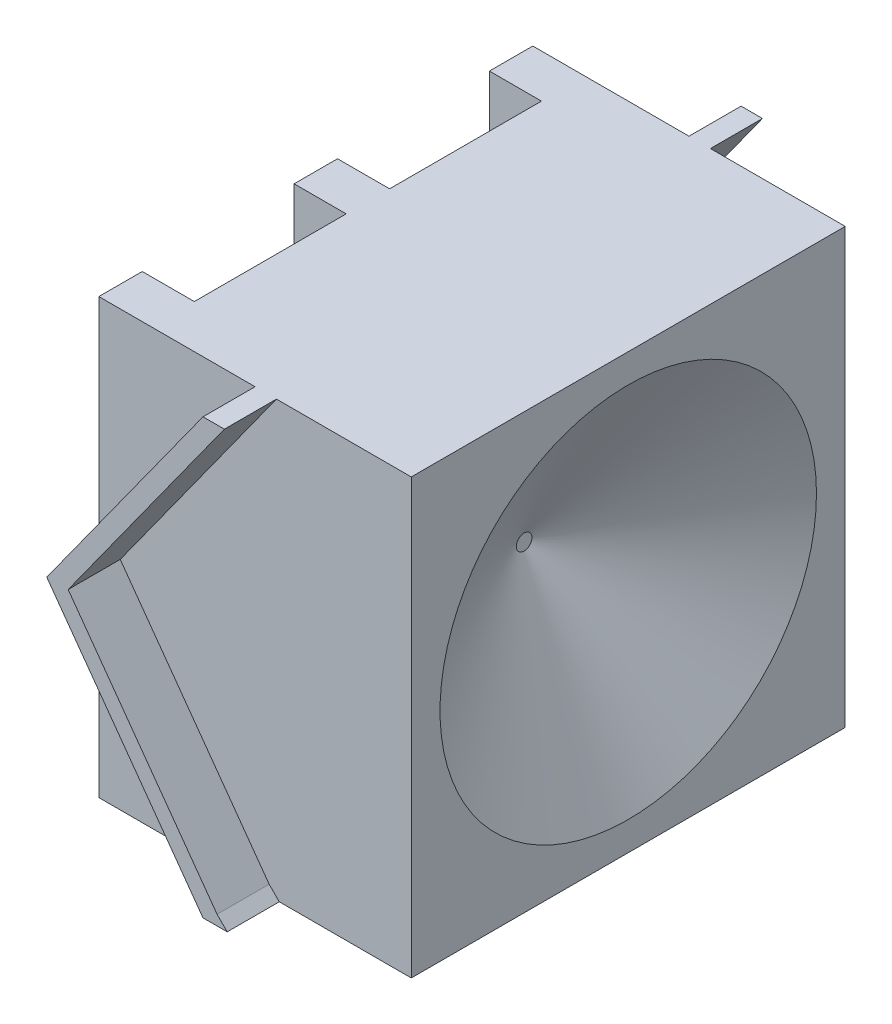
SolidWorks part; units mm, degrees
ref_plane "Front Plane" through (0, 0, 0) normal (0, 0, 1) x (1, 0, 0)
ref_plane "Top Plane" through (0, 0, 0) normal (0, 1, 0) x (1, 0, 0)
ref_plane "Right Plane" through (0, 0, 0) normal (1, 0, 0) x (0, 0, -1)
sketch "Çizim1" plane through (0, 0, 0) normal (1, 0, 0) x (0, 0, -1)
  line L1 (-125, 125) -> (125, 125)
  line L2 (-125, 125) -> (-125, -125)
  line L3 (-125, -125) -> (125, -125)
  line L4 (125, 125) -> (125, -125)
  line L5 (-125, 125) -> (125, -125) construction
  line L6 (-125, -125) -> (125, 125) construction
  point P0 (0, 0)
  dimension "D1" = 250
  dimension "D2" = 250
extrude "Yükseklik-Ekstrüzyon1" add sketch "Çizim1" along normal blind 150
sketch "Çizim2" plane through (150, 0, 0) normal (1, 0, 0) x (0, 0, -1)
  circle A0 centre (0, 0) radius 108.4351
extrude "Kes-Ekstrüzyon1" cut sketch "Çizim2" against normal blind 60 draft 60
sketch "Çizim3" plane through (0, 0, 0) normal (-1, 0, 0) x (0, 0, 1)
  line L0 (125, -125) -> (-125, -125) construction
  line L1 (-125, 125) -> (-100, 125)
  line L2 (-125, 125) -> (-125, -125)
  line L3 (-125, -125) -> (-100, -125)
  line L4 (-100, 125) -> (-100, -125)
  line L5 (-125, 125) -> (125, 125) construction
  line L6 (125, 125) -> (100, 125)
  line L7 (125, 125) -> (125, -125)
  line L8 (125, -125) -> (100, -125)
  line L9 (100, 125) -> (100, -125)
  line L10 (125, 125) -> (125, -125) construction
  line L12 (-12.5, -125) -> (12.5, -125)
  line L13 (-12.5, -125) -> (-12.5, 125)
  line L14 (-12.5, 125) -> (12.5, 125)
  line L15 (12.5, -125) -> (12.5, 125)
  line L16 (-12.5, -125) -> (12.5, 125) construction
  line L17 (-12.5, 125) -> (12.5, -125) construction
  point P15 (0, 0)
  dimension "D1" = 25
  dimension "D2" = 25
  dimension "D3" = 25
extrude "Yükseklik-Ekstrüzyon2" add sketch "Çizim3" along normal blind 30
sketch "Çizim4" plane through (0, 0, 125) normal (0, 0, 1) x (1, 0, 0)
  line L0 (60, 125) -> (-30, 0)
  line L1 (150, 125) -> (-30, 125) construction
  line L2 (-30, -125) -> (-30, 125) construction
  line L3 (-30, 0) -> (60, -125)
  line L4 (150, -125) -> (-30, -125) construction
  line L10 (68.1153, 119.157) -> (-17.6777, 0)
  line L11 (-17.6777, 0) -> (68.1153, -119.157)
  line L12 (68.1153, 119.157) -> (72.3223, 125)
  line L13 (68.1153, -119.157) -> (73.9584, -125)
  line L14 (60, -125) -> (73.9584, -125)
  line L15 (60, 125) -> (72.3223, 125)
  dimension "D1" = 10
extrude "Yükseklik-Ekstrüzyon3" add sketch "Çizim4" against normal blind 280 and the other way blind 30
